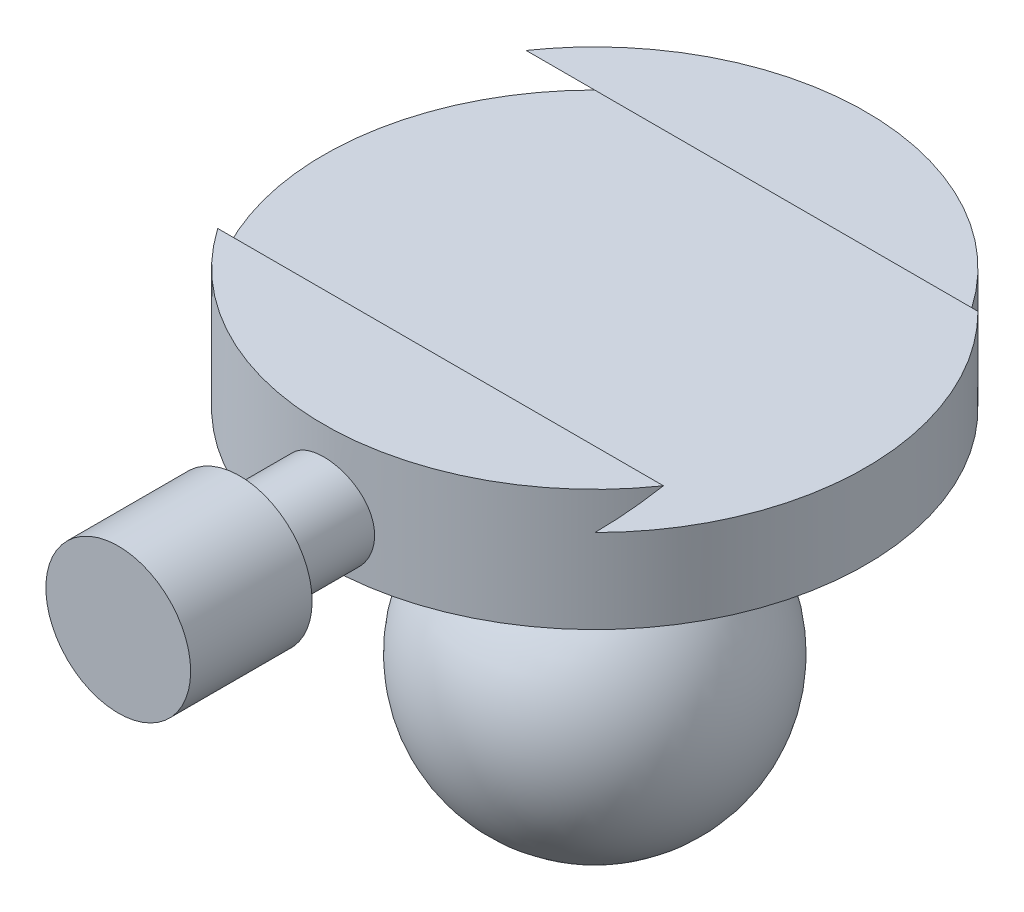
SolidWorks part; units mm, degrees
ref_plane "前视基准面" through (0, 0, 0) normal (0, 0, 1) x (1, 0, 0)
ref_plane "上视基准面" through (0, 0, 0) normal (0, 1, 0) x (1, 0, 0)
ref_plane "右视基准面" through (0, 0, 0) normal (1, 0, 0) x (0, 0, -1)
sketch "草图1" plane through (0, 0, 0) normal (0, 0, 1) x (1, 0, 0)
  line L0 (0, -16) -> (0, 22.7376)
  line L2 (7.3, 17.2376) -> (7.3, 14.2376)
  line L3 (7.3, 17.2376) -> (7, 17.2376)
  line L4 (7, 17.2376) -> (7, 22.7376)
  line L5 (7, 22.7376) -> (0, 22.7376)
  arc A0 (0, -16) -> (7.3, 14.2376) centre (0, 0) ccw
  dimension "D1" = 16
  dimension "D2" = 7.3
  dimension "D3" = 3
  dimension "D4" = 5.5
  dimension "D5" = 0.3
revolve "旋转1" add sketch "草图1" angle 360 about L0
sketch "草图2" plane through (0, 22.7376, 0) normal (0, 1, 0) x (1, 0, 0)
  circle A0 centre (0, 0) radius 29
  dimension "D1" = 58
extrude "凸台-拉伸1" add sketch "草图2" along normal blind 13
sketch "草图3" plane through (0, 0, 0) normal (0, 0, 1) x (1, 0, 0)
  line L0 (-7, 22.7376) -> (7, 22.7376) construction
  line L1 (0, 0) -> (0, 27.7376) construction
  circle A0 centre (0, 27.7376) radius 5
  dimension "D1" = 10
  dimension "D2" = 5
extrude "凸台-拉伸2" add sketch "草图3" along normal blind 37
sketch "草图4" plane through (0, 0, 37) normal (0, 0, 1) x (1, 0, 0)
  circle A0 centre (0, 27.7376) radius 5
extrude "凸台-拉伸3" add sketch "草图4" along normal blind 1 draft 70 draft outward yes
sketch "草图5" plane through (0, 0, 38) normal (0, 0, 1) x (1, 0, 0)
  circle A0 centre (0, 27.7376) radius 7.7475
  dimension "D1" = 15.495
extrude "凸台-拉伸4" add sketch "草图5" along normal blind 13
sketch "草图6" plane through (0, 0, 0) normal (1, 0, 0) x (0, 0, -1)
  line L0 (-16.5, 35.7376) -> (-20.5, 31.7376)
  line L1 (29, 35.7376) -> (-29, 35.7376) construction
  line L2 (-20.5, 31.7376) -> (20.5, 31.7376)
  line L3 (20.5, 31.7376) -> (16.5, 35.7376)
  line L4 (0, 31.7376) -> (0, 0) construction
  line L5 (-16.5, 35.7376) -> (16.5, 35.7376)
  dimension "D1" = 41
  dimension "D2" = 4
  dimension "D3" = 45
extrude "切除-拉伸1" cut sketch "草图6" against normal through all both and the other way through all contours L5 L0 L2 L3
